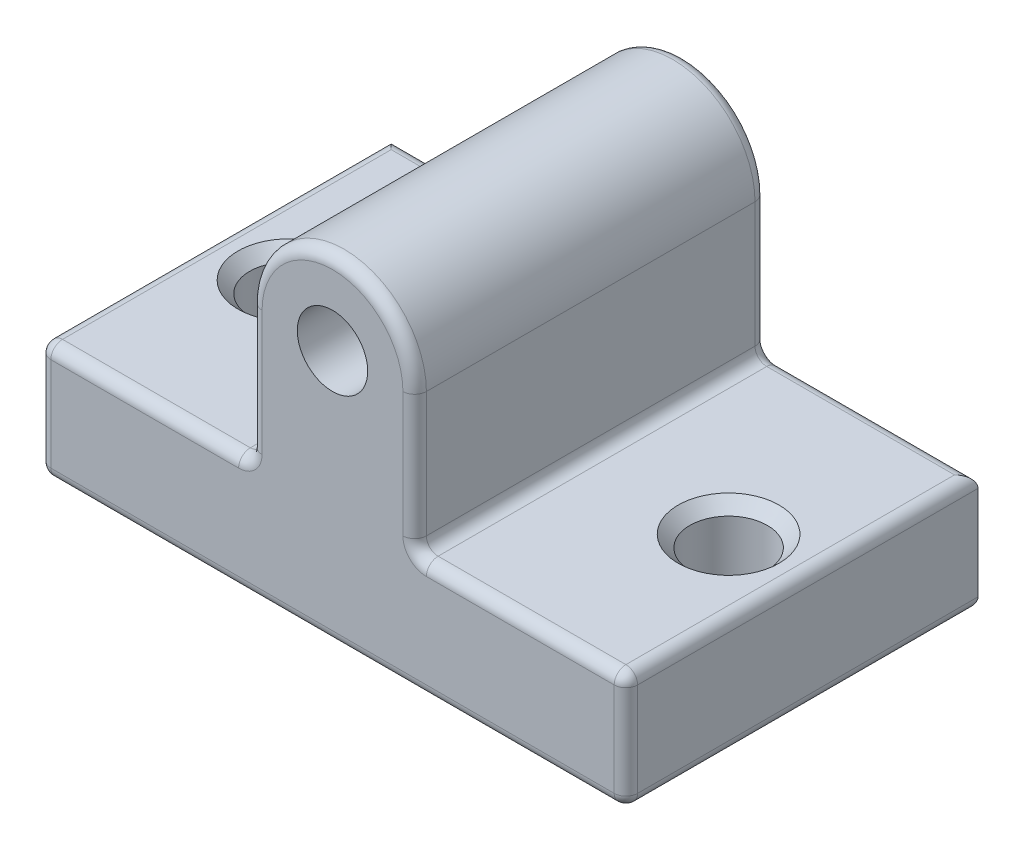
SolidWorks part; units mm, degrees
ref_plane "Front Plane" through (0, 0, 0) normal (0, 0, 1) x (1, 0, 0)
ref_plane "Top Plane" through (0, 0, 0) normal (0, 1, 0) x (1, 0, 0)
ref_plane "Right Plane" through (0, 0, 0) normal (1, 0, 0) x (0, 0, -1)
sketch "Sketch1" plane through (0, 0, 0) normal (0, 0, 1) x (1, 0, 0)
  line L1 (25, -5) -> (-25, -5)
  line L2 (25, -5) -> (25, 5)
  line L3 (25, 5) -> (-25, 5)
  line L4 (-25, -5) -> (-25, 5)
  line L5 (25, -5) -> (-25, 5) construction
  line L6 (25, 5) -> (-25, -5) construction
  point P0 (0, 0)
  dimension "D1" = 50
  dimension "D2" = 10
extrude "Boss-Extrude1" add sketch "Sketch1" along normal blind 30
sketch "Sketch2" plane through (0, 0, 30) normal (0, 0, 1) x (1, 0, 0)
  line L0 (-7, 5) -> (-7, 16.6518)
  line L1 (25, 5) -> (-25, 5) construction
  line L2 (7, 16.6518) -> (7, 5)
  line L3 (7, 5) -> (-7, 5)
  arc A0 (-7, 16.6518) -> (7, 16.6518) centre (0, 16.6518) cw
  circle A1 centre (0, 16.6518) radius 3
  dimension "D1" = 11.6518
  dimension "D2" = 7
  dimension "D3" = 6
extrude "Boss-Extrude2" add sketch "Sketch2" against normal up to surface (30 mm away) up to face at (0, 0, 0)
sketch "Sketch3" plane through (0, 5, 0) normal (0, 1, 0) x (1, 0, 0)
  line L0 (-25, -30) -> (-25, 0) construction
  line L1 (25, -30) -> (25, 0) construction
  circle A0 centre (-18.75, -15) radius 3.3
  circle A1 centre (18.75, -15) radius 3.3
  point P9 (-25, -15)
  dimension "D1" = 6.25
  dimension "D2" = 6.25
  dimension "D3" = 6.6
extrude "Cut-Extrude1" cut sketch "Sketch3" against normal up to next
fillet "Fillet1" radius 1 20 edges at (0, 23.6518, 0) (0, 23.6518, 30) (7, 10.8259, 0) (7, 10.8259, 30) (-7, 10.8259, 0) (-7, 10.8259, 30) (25, 0, 30) (-25, 0, 30) (-25, -5, 15) (25, -5, 15) (0, -5, 0) (0, -5, 30) (25, 5, 15) (7, 5, 15) (16, 5, 0) (16, 5, 30) (-25, 5, 15) (-16, 5, 0) (-7, 5, 15) (-16, 5, 30)
chamfer "Chamfer1" distance 1 angle 45 2 edges at (-22.05, 5, 15) (15.45, 5, 15)
